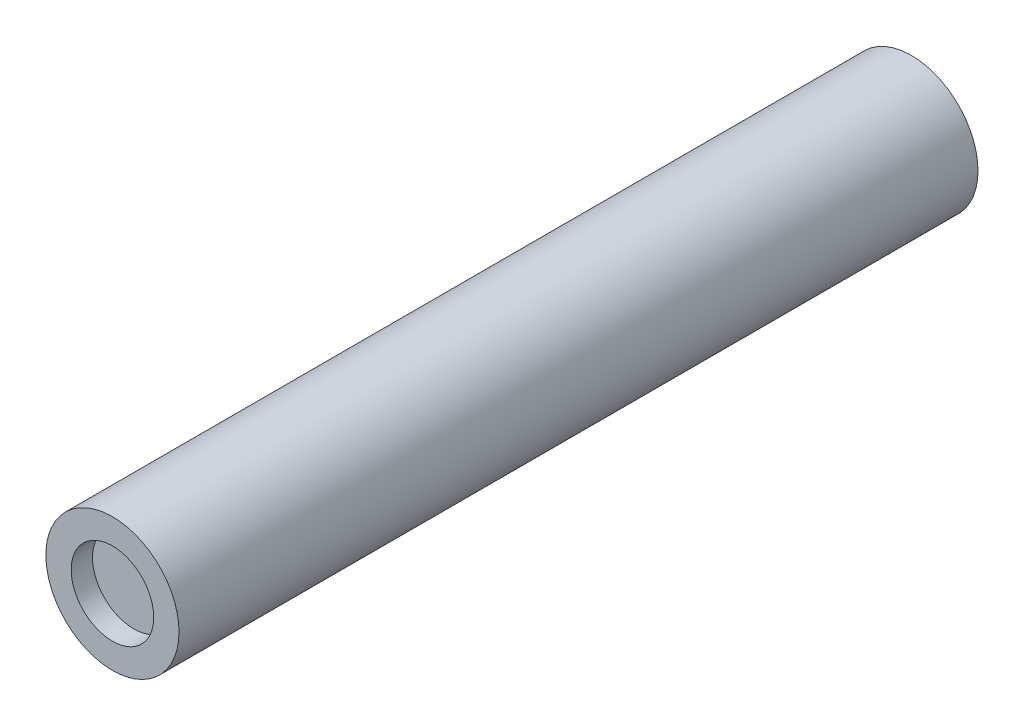
SolidWorks part; units mm, degrees
ref_plane "Plano frontal" through (0, 0, 0) normal (0, 0, 1) x (1, 0, 0)
ref_plane "Plano superior" through (0, 0, 0) normal (0, 1, 0) x (1, 0, 0)
ref_plane "Plano direito" through (0, 0, 0) normal (1, 0, 0) x (0, 0, -1)
sketch "Esboço1" plane through (0, 0, 0) normal (0, 0, 1) x (1, 0, 0)
  circle A0 centre (-47.0621, 23.3146) radius 5
extrude "Ressalto-extrusão1" add sketch "Esboço1" along normal blind 60
sketch "Esboço2" plane through (0, 0, 60) normal (0, 0, 1) x (1, 0, 0)
  circle A0 centre (-47.0621, 23.3146) radius 3.1
extrude "Corte-extrusão1" cut sketch "Esboço2" against normal blind 1.6
sketch "Esboço4" plane through (0, 0, 0) normal (0, 0, -1) x (-1, 0, 0)
  circle A0 centre (47.0621, 23.3146) radius 3.1
extrude "Corte-extrusão2" cut sketch "Esboço4" against normal blind 1.6
